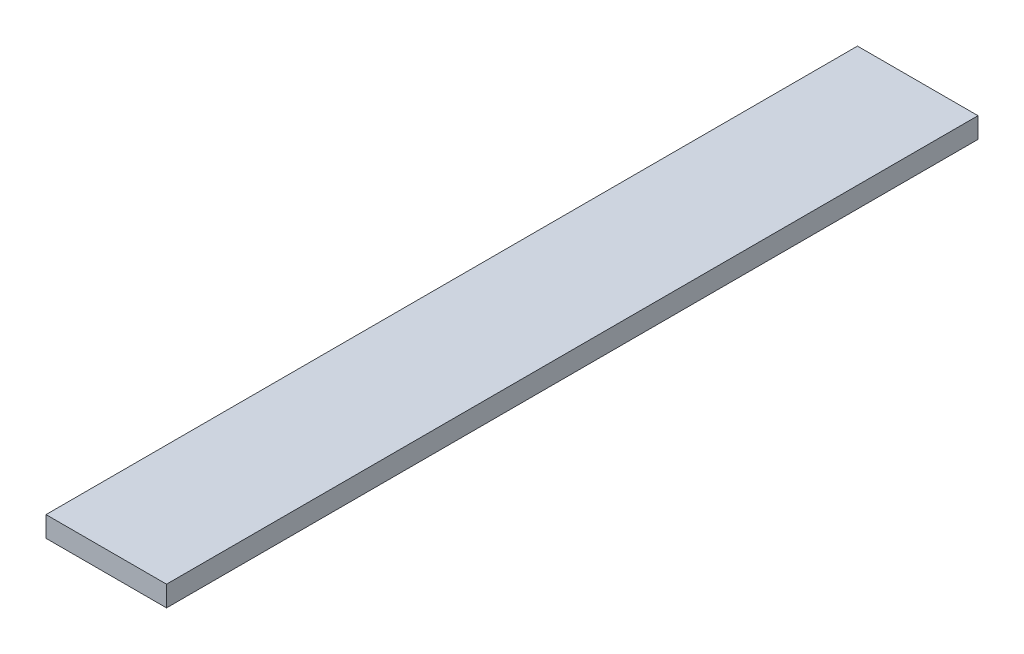
SolidWorks part; units mm, degrees
ref_plane "Plano frontal" through (0, 0, 0) normal (0, 0, 1) x (1, 0, 0)
ref_plane "Plano superior" through (0, 0, 0) normal (0, 1, 0) x (1, 0, 0)
ref_plane "Plano direito" through (0, 0, 0) normal (1, 0, 0) x (0, 0, -1)
sketch "Esboço1" plane through (0, 0, 0) normal (0, 0, 1) x (1, 0, 0)
  line L1 (47.9, 8.175) -> (-47.9, 8.175)
  line L2 (47.9, 8.175) -> (47.9, -8.175)
  line L3 (47.9, -8.175) -> (-47.9, -8.175)
  line L4 (-47.9, 8.175) -> (-47.9, -8.175)
  line L5 (47.9, 8.175) -> (-47.9, -8.175) construction
  line L6 (47.9, -8.175) -> (-47.9, 8.175) construction
  point P0 (0, 0)
  dimension "D1" = 95.8
  dimension "D2" = 16.35
extrude "Ressalto-extrusão1" add sketch "Esboço1" along normal blind 645
